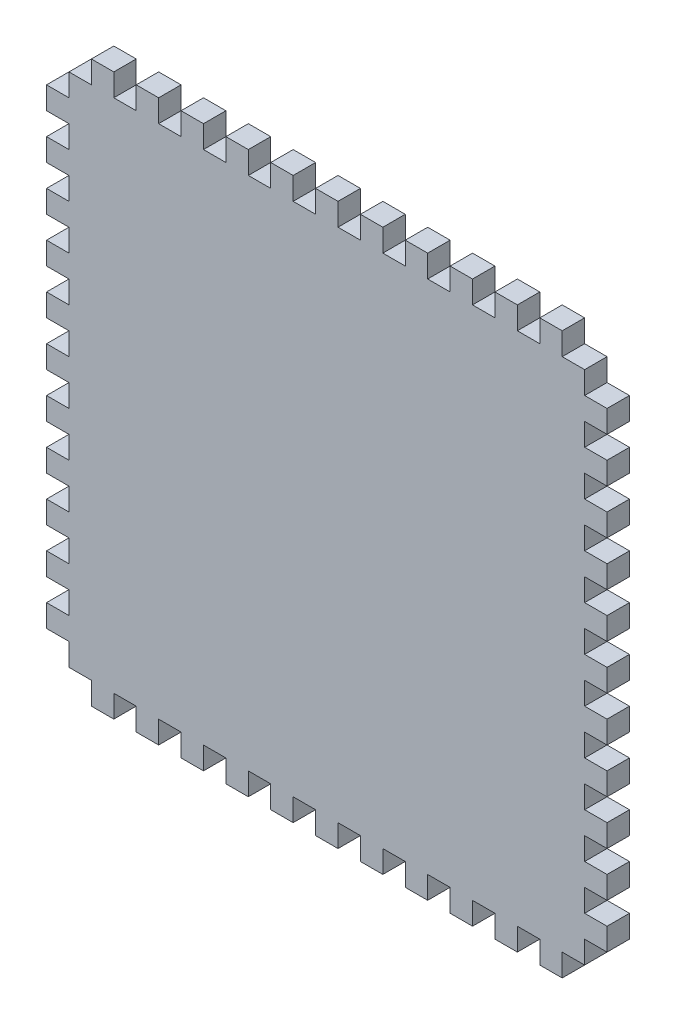
SolidWorks part; units mm, degrees
ref_plane "Front Plane" through (0, 0, 0) normal (0, 0, 1) x (1, 0, 0)
ref_plane "Top Plane" through (0, 0, 0) normal (0, 1, 0) x (1, 0, 0)
ref_plane "Right Plane" through (0, 0, 0) normal (1, 0, 0) x (0, 0, -1)
sketch "Sketch1" plane through (0, 0, 0) normal (0, 0, 1) x (1, 0, 0)
  line L276 (219, 51) -> (219, 48)
  line L277 (219, 48) -> (216, 48)
  line L278 (216, 48) -> (216, 45)
  line L279 (216, 45) -> (219, 45)
  line L280 (219, 45) -> (219, 42)
  line L281 (219, 42) -> (216, 42)
  line L282 (216, 42) -> (216, 39)
  line L283 (216, 39) -> (219, 39)
  line L284 (219, 39) -> (219, 36)
  line L285 (219, 36) -> (216, 36)
  line L286 (216, 36) -> (216, 33)
  line L287 (216, 33) -> (219, 33)
  line L288 (219, 33) -> (219, 30)
  line L289 (219, 30) -> (216, 30)
  line L290 (216, 30) -> (216, 27)
  line L291 (216, 27) -> (219, 27)
  line L292 (219, 27) -> (219, 24)
  line L293 (219, 24) -> (216, 24)
  line L294 (216, 24) -> (216, 21)
  line L295 (216, 21) -> (219, 21)
  line L296 (219, 21) -> (219, 18)
  line L297 (219, 18) -> (216, 18)
  line L298 (216, 18) -> (216, 15)
  line L299 (216, 15) -> (219, 15)
  line L300 (219, 15) -> (219, 12)
  line L301 (219, 12) -> (216, 12)
  line L302 (216, 12) -> (216, 9)
  line L303 (216, 9) -> (219, 9)
  line L304 (219, 9) -> (219, 6)
  line L305 (219, 6) -> (222, 6)
  line L306 (222, 6) -> (222, 3)
  line L307 (222, 3) -> (225, 3)
  line L308 (225, 3) -> (225, 6)
  line L309 (225, 6) -> (228, 6)
  line L310 (228, 6) -> (228, 3)
  line L311 (228, 3) -> (231, 3)
  line L312 (231, 3) -> (231, 6)
  line L313 (231, 6) -> (234, 6)
  line L314 (234, 6) -> (234, 3)
  line L315 (234, 3) -> (237, 3)
  line L316 (237, 3) -> (237, 6)
  line L317 (237, 6) -> (240, 6)
  line L318 (240, 6) -> (240, 3)
  line L319 (240, 3) -> (243, 3)
  line L320 (243, 3) -> (243, 6)
  line L321 (243, 6) -> (246, 6)
  line L322 (246, 6) -> (246, 3)
  line L323 (246, 3) -> (249, 3)
  line L324 (249, 3) -> (249, 6)
  line L325 (249, 6) -> (252, 6)
  line L326 (252, 6) -> (252, 3)
  line L327 (252, 3) -> (255, 3)
  line L328 (255, 3) -> (255, 6)
  line L329 (255, 6) -> (258, 6)
  line L330 (258, 6) -> (258, 3)
  line L331 (258, 3) -> (261, 3)
  line L332 (261, 3) -> (261, 6)
  line L333 (261, 6) -> (264, 6)
  line L334 (264, 6) -> (264, 3)
  line L335 (264, 3) -> (267, 3)
  line L336 (267, 3) -> (267, 6)
  line L337 (267, 6) -> (270, 6)
  line L338 (270, 6) -> (270, 3)
  line L339 (270, 3) -> (273, 3)
  line L340 (273, 3) -> (273, 6)
  line L341 (273, 6) -> (276, 6)
  line L342 (276, 6) -> (276, 3)
  line L343 (276, 3) -> (279, 3)
  line L344 (279, 3) -> (279, 6)
  line L345 (279, 6) -> (282, 6)
  line L346 (282, 6) -> (282, 3)
  line L347 (282, 3) -> (285, 3)
  line L348 (285, 3) -> (285, 6)
  line L349 (285, 6) -> (288, 6)
  line L350 (288, 6) -> (288, 9)
  line L351 (288, 9) -> (291, 9)
  line L352 (291, 9) -> (291, 12)
  line L353 (291, 12) -> (288, 12)
  line L354 (288, 12) -> (288, 15)
  line L355 (288, 15) -> (291, 15)
  line L356 (291, 15) -> (291, 18)
  line L357 (291, 18) -> (288, 18)
  line L358 (288, 18) -> (288, 21)
  line L359 (288, 21) -> (291, 21)
  line L360 (291, 21) -> (291, 24)
  line L361 (291, 24) -> (288, 24)
  line L362 (288, 24) -> (288, 27)
  line L363 (288, 27) -> (291, 27)
  line L364 (291, 27) -> (291, 30)
  line L365 (291, 30) -> (288, 30)
  line L366 (288, 30) -> (288, 33)
  line L367 (288, 33) -> (291, 33)
  line L368 (291, 33) -> (291, 36)
  line L369 (291, 36) -> (288, 36)
  line L370 (288, 36) -> (288, 39)
  line L371 (288, 39) -> (291, 39)
  line L372 (291, 39) -> (291, 42)
  line L373 (291, 42) -> (288, 42)
  line L374 (288, 42) -> (288, 45)
  line L375 (288, 45) -> (291, 45)
  line L376 (291, 45) -> (291, 48)
  line L377 (291, 48) -> (288, 48)
  line L378 (288, 48) -> (288, 51)
  line L379 (288, 51) -> (291, 51)
  line L380 (291, 51) -> (291, 54)
  line L381 (291, 54) -> (288, 54)
  line L382 (288, 54) -> (288, 57)
  line L383 (288, 57) -> (291, 57)
  line L384 (291, 57) -> (291, 60)
  line L385 (291, 60) -> (288, 60)
  line L386 (288, 60) -> (288, 63)
  line L387 (288, 63) -> (291, 63)
  line L388 (291, 63) -> (291, 66)
  line L389 (291, 66) -> (288, 66)
  line L390 (288, 66) -> (288, 69)
  line L391 (288, 69) -> (291, 69)
  line L392 (291, 69) -> (291, 72)
  line L393 (291, 72) -> (288, 72)
  line L394 (288, 72) -> (288, 75)
  line L395 (288, 75) -> (285, 75)
  line L396 (285, 75) -> (285, 78)
  line L397 (285, 78) -> (282, 78)
  line L398 (282, 78) -> (282, 75)
  line L399 (282, 75) -> (279, 75)
  line L400 (279, 75) -> (279, 78)
  line L401 (279, 78) -> (276, 78)
  line L402 (276, 78) -> (276, 75)
  line L403 (276, 75) -> (273, 75)
  line L404 (273, 75) -> (273, 78)
  line L405 (273, 78) -> (270, 78)
  line L406 (270, 78) -> (270, 75)
  line L407 (270, 75) -> (267, 75)
  line L408 (267, 75) -> (267, 78)
  line L409 (267, 78) -> (264, 78)
  line L410 (264, 78) -> (264, 75)
  line L411 (264, 75) -> (261, 75)
  line L412 (261, 75) -> (261, 78)
  line L413 (261, 78) -> (258, 78)
  line L414 (258, 78) -> (258, 75)
  line L415 (258, 75) -> (255, 75)
  line L416 (255, 75) -> (255, 78)
  line L417 (255, 78) -> (252, 78)
  line L418 (252, 78) -> (252, 75)
  line L419 (252, 75) -> (249, 75)
  line L420 (249, 75) -> (249, 78)
  line L421 (249, 78) -> (246, 78)
  line L422 (246, 78) -> (246, 75)
  line L423 (246, 75) -> (243, 75)
  line L424 (243, 75) -> (243, 78)
  line L425 (243, 78) -> (240, 78)
  line L426 (240, 78) -> (240, 75)
  line L427 (240, 75) -> (237, 75)
  line L428 (237, 75) -> (237, 78)
  line L429 (237, 78) -> (234, 78)
  line L430 (234, 78) -> (234, 75)
  line L431 (234, 75) -> (231, 75)
  line L432 (231, 75) -> (231, 78)
  line L433 (231, 78) -> (228, 78)
  line L434 (228, 78) -> (228, 75)
  line L435 (228, 75) -> (225, 75)
  line L436 (225, 75) -> (225, 78)
  line L437 (225, 78) -> (222, 78)
  line L438 (222, 78) -> (222, 75)
  line L439 (222, 75) -> (219, 75)
  line L440 (219, 75) -> (219, 72)
  line L441 (219, 72) -> (216, 72)
  line L442 (216, 72) -> (216, 69)
  line L443 (216, 69) -> (219, 69)
  line L444 (219, 69) -> (219, 66)
  line L445 (219, 66) -> (216, 66)
  line L446 (216, 66) -> (216, 63)
  line L447 (216, 63) -> (219, 63)
  line L448 (219, 63) -> (219, 60)
  line L449 (219, 60) -> (216, 60)
  line L450 (216, 60) -> (216, 57)
  line L451 (216, 57) -> (219, 57)
  line L452 (219, 57) -> (219, 54)
  line L453 (219, 54) -> (216, 54)
  line L454 (216, 54) -> (216, 51)
  line L455 (216, 51) -> (219, 51)
extrude "Boss-Extrude1" add sketch "Sketch1" along normal blind 3
